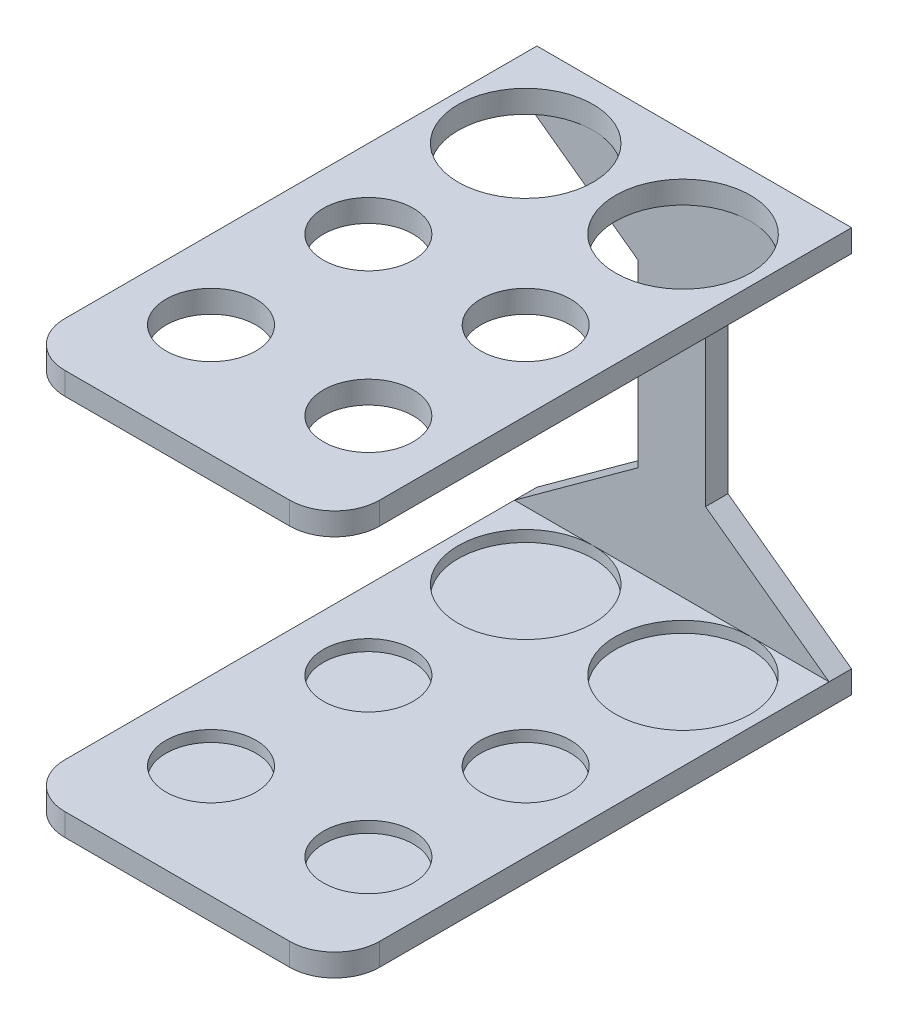
SolidWorks part; units mm, degrees
ref_plane "Front Plane" through (0, 0, 0) normal (0, 0, 1) x (1, 0, 0)
ref_plane "Top Plane" through (0, 0, 0) normal (0, 1, 0) x (1, 0, 0)
ref_plane "Right Plane" through (0, 0, 0) normal (1, 0, 0) x (0, 0, -1)
sketch "Sketch1" plane through (0, 0, 0) normal (1, 0, 0) x (0, 0, -1)
  line L1 (0, 0) -> (6.35, 0)
  line L2 (0, 0) -> (0, 114.3)
  line L3 (0, 114.3) -> (6.35, 114.3)
  line L4 (6.35, 0) -> (6.35, 114.3)
  line L5 (0, 114.3) -> (-139.7, 114.3)
  line L6 (0, 114.3) -> (0, 107.95)
  line L7 (0, 107.95) -> (-139.7, 107.95)
  line L8 (-139.7, 114.3) -> (-139.7, 107.95)
  line L9 (0, 0) -> (-139.7, 0)
  line L10 (0, 0) -> (0, 6.35)
  line L11 (0, 6.35) -> (-139.7, 6.35)
  line L12 (-139.7, 0) -> (-139.7, 6.35)
  dimension "D1" = 101.6
  dimension "D2" = 6.35
  dimension "D3" = 6.35
  dimension "D4" = 6.35
  dimension "D5" = 139.7
extrude "Boss-Extrude1" add sketch "Sketch1" along normal blind 88.9 contours L5 L8 L7 L2 | L1 L4 L3 L2 | L12 L9 L2 L11
sketch "Sketch2" plane through (0, 114.3, 0) normal (0, 1, 0) x (1, 0, 0)
  line L0 (88.9, 6.35) -> (0, 6.35) construction
  line L4 (22.225, -19.05) -> (22.225, -107.95) construction
  line L5 (22.225, -19.05) -> (66.675, -19.05) construction
  line L6 (66.675, -19.05) -> (66.675, -107.95) construction
  line L7 (22.225, -107.95) -> (66.675, -107.95) construction
  line L8 (22.225, -19.05) -> (66.675, -107.95) construction
  line L9 (66.675, -19.05) -> (22.225, -107.95) construction
  circle A0 centre (66.675, -19.05) radius 19.05
  circle A1 centre (66.675, -63.5) radius 12.7
  circle A2 centre (66.675, -107.95) radius 12.7
  circle A3 centre (22.225, -107.95) radius 12.7
  circle A4 centre (22.225, -63.5) radius 12.7
  circle A5 centre (22.225, -19.05) radius 19.05
  point P0 (59.4829, -93.7381)
  point P9 (44.45, -63.5)
  dimension "D1" = 44.45
  dimension "D3" = 38.1
  dimension "D4" = 25.4
  dimension "D2" = 88.9
  dimension "D5" = 25.4
extrude "Cut-Extrude1" cut sketch "Sketch2" against normal blind 111.125
sketch "Sketch4" plane through (0, 0, 0) normal (0, 0, 1) x (1, 0, 0)
  line L4 (34.925, 31.75) -> (34.925, 82.55)
  line L9 (53.975, 82.55) -> (53.975, 31.75)
  line L11 (34.925, 31.75) -> (0, 6.35)
  line L12 (88.9, 6.35) -> (53.975, 31.75)
  line L13 (53.975, 82.55) -> (88.9, 107.95)
  line L14 (88.9, 107.95) -> (88.9, 6.35)
  line L15 (34.925, 82.55) -> (0, 107.95)
  line L16 (0, 107.95) -> (0, 6.35)
  point P12 (0, 0)
  dimension "D1" = 19.05
  dimension "D2" = 50.8
extrude "Cut-Extrude3" cut sketch "Sketch4" against normal through all both and the other way through all
fillet "Fillet1" radius 12.7 4 edges at (88.9, 111.125, 139.7) (0, 3.175, 139.7) (0, 111.125, 139.7) (88.9, 3.175, 139.7)
